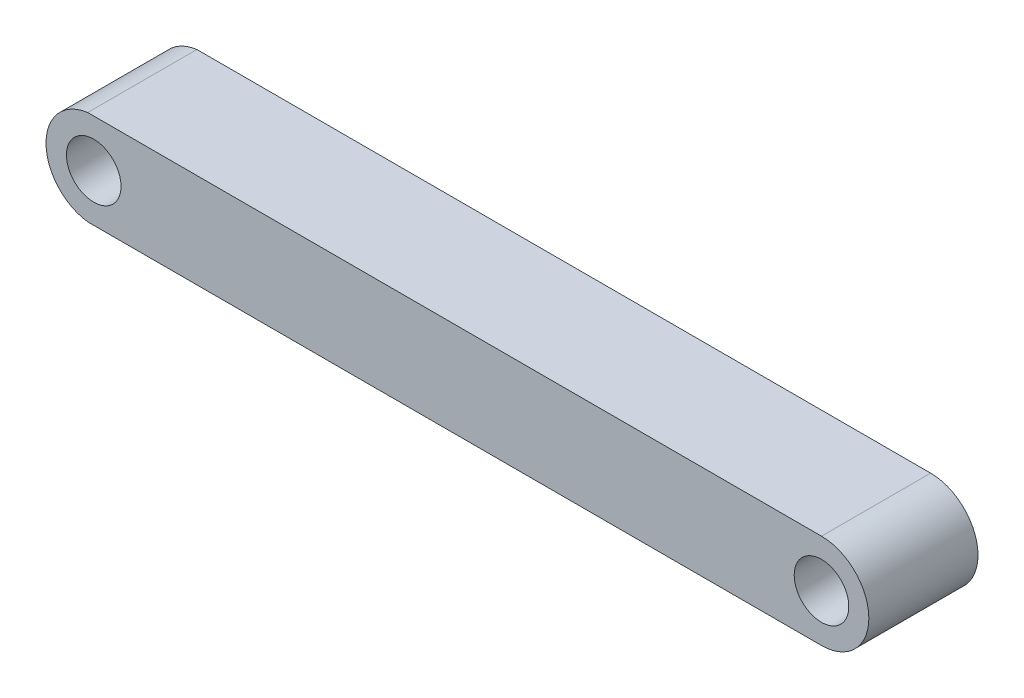
SolidWorks part; units mm, degrees
ref_plane "Front Plane" through (0, 0, 0) normal (0, 0, 1) x (1, 0, 0)
ref_plane "Top Plane" through (0, 0, 0) normal (0, 1, 0) x (1, 0, 0)
ref_plane "Right Plane" through (0, 0, 0) normal (1, 0, 0) x (0, 0, -1)
sketch "Sketch1" plane through (0, 0, 0) normal (0, 0, 1) x (1, 0, 0)
  line L1 (-21.2997, 8.5838) -> (106.7491, 8.5838)
  line L3 (-21.2997, -7.9444) -> (106.7491, -7.9444)
  arc A0 (-21.2997, 8.5838) -> (-21.2997, -7.9444) centre (-20.2509, 0.3197) ccw
  circle A2 centre (-20.2509, 0.3197) radius 4.7625
  arc A4 (106.7491, 8.5838) -> (106.7491, -7.9444) centre (106.7491, 0.3197) cw
  circle A5 centre (106.7491, 0.3197) radius 4.7625
  point P8 (0, 0)
  point P9 (0, 0)
  dimension "D1" = 9.525
  dimension "D2" = 9.525
  dimension "D3" = 127
extrude "Boss-Extrude1" add sketch "Sketch1" along normal blind 19.05
